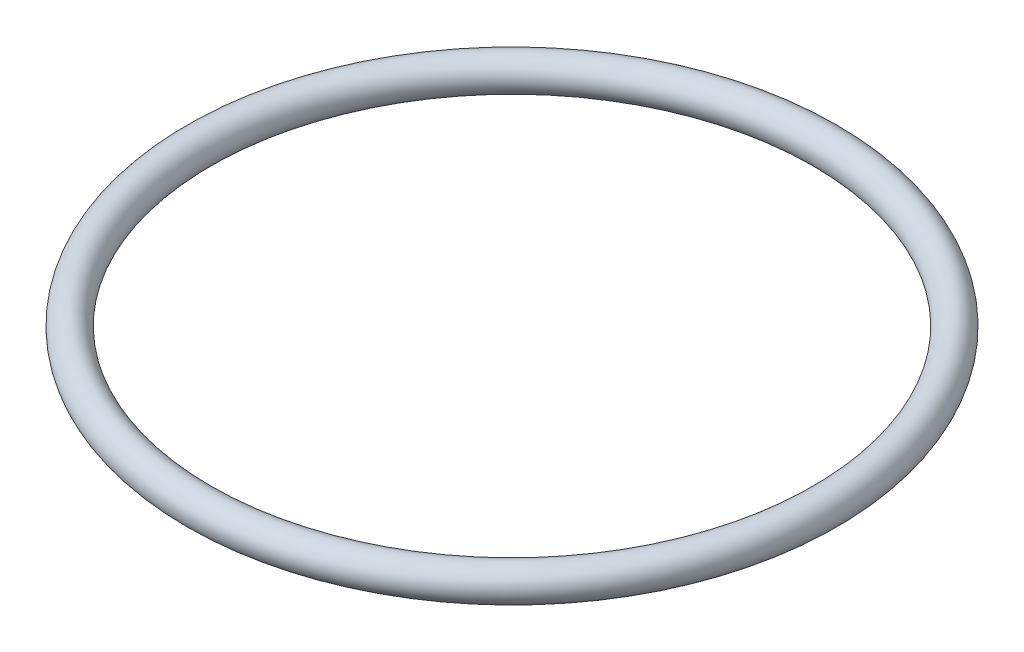
SolidWorks part; units mm, degrees
ref_plane "Front Plane" through (0, 0, 0) normal (0, 0, 1) x (1, 0, 0)
ref_plane "Top Plane" through (0, 0, 0) normal (0, 1, 0) x (1, 0, 0)
ref_plane "Right Plane" through (0, 0, 0) normal (1, 0, 0) x (0, 0, -1)
sketch "Sketch1" plane through (0, 0, 0) normal (0, 0, 1) x (1, 0, 0)
  line L0 (0, 0) -> (50000, 0) construction
  line L1 (0, 0) -> (0, 50000) construction
  circle A0 centre (16.6243, 0) radius 0.889
  point P6 (15.7353, 0)
  dimension "D1" = 1.778
  dimension "D2" = 15.7353
revolve "Revolve1" add sketch "Sketch1" angle 360 about L1
sketch "Sketch2" plane through (0, 0, 0) normal (0, 1, 0) x (1, 0, 0)
  circle A0 centre (0, 0) radius 17.5133
  circle A1 centre (0, 0) radius 17.5133 construction
